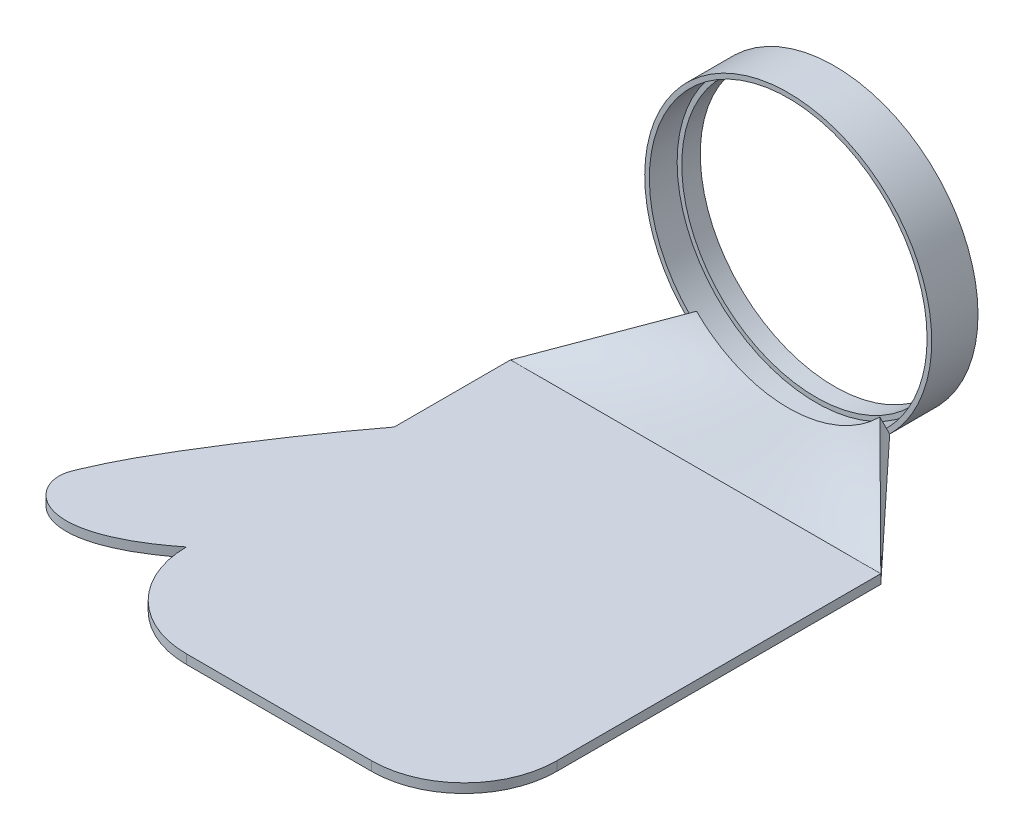
SolidWorks part; units mm, degrees
ref_plane "Front Plane" through (0, 0, 0) normal (0, 0, 1) x (1, 0, 0)
ref_plane "Top Plane" through (0, 0, 0) normal (0, 1, 0) x (1, 0, 0)
ref_plane "Right Plane" through (0, 0, 0) normal (1, 0, 0) x (0, 0, -1)
sketch "Sketch1" plane through (0, 0, 0) normal (0, 0, 1) x (1, 0, 0)
  circle A0 centre (0, 0) radius 15
  circle A1 centre (0, 0) radius 14.5
  dimension "D1" = 30
  dimension "D2" = 0.5
extrude "Boss-Extrude1" add sketch "Sketch1" along normal blind 2
sketch "Sketch2" plane through (0, 0, 2) normal (0, 0, 1) x (1, 0, 0)
  circle A0 centre (0, 0) radius 15
  circle A1 centre (0, 0) radius 15.5
  dimension "D1" = 0.5
extrude "Boss-Extrude2" add sketch "Sketch2" along normal blind 3 and the other way blind 2
sketch "Sketch3" plane through (0, 0, 5) normal (0, 0, 1) x (1, 0, 0)
  line L0 (-9.8995, -9.8995) -> (-10.9602, -10.9602)
  line L1 (9.8995, -9.8995) -> (10.9602, -10.9602)
  line L2 (0, -14) -> (0, -15.5) construction
  arc A0 (-10.9602, -10.9602) -> (10.9602, -10.9602) centre (0, 0) ccw
  arc A1 (-9.8995, -9.8995) -> (9.8995, -9.8995) centre (0, 0) ccw
  dimension "D1" = 28
  dimension "D2" = 90
  dimension "D3" = 45
ref_plane "Plane1" through (0, 0, 15) normal (0, 0, 1) x (1, 0, 0)
sketch "Sketch4" plane through (0, 0, 15) normal (0, 0, 1) x (1, 0, 0)
  line L1 (-20, -15.5) -> (20, -15.5)
  line L2 (-20, -15.5) -> (-20, -14.5)
  line L3 (-20, -14.5) -> (20, -14.5)
  line L4 (20, -15.5) -> (20, -14.5)
  dimension "D1" = 40
  dimension "D2" = 1
  dimension "2" = 20
loft "Loft1" add profiles "Sketch4", "Sketch3"
sketch "Sketch5" plane through (0, 0, 15) normal (0, 0, 1) x (1, 0, 0)
  line L4 (-20, -14.5) -> (-20, -15.5)
  line L5 (-20, -15.5) -> (20, -15.5)
  line L6 (20, -15.5) -> (20, -14.5)
  line L7 (20, -14.5) -> (-20, -14.5)
  line L8 (-20, -14.5) -> (-20, -15.5)
  line L9 (-20, -15.5) -> (20, -15.5)
  line L10 (20, -15.5) -> (20, -14.5)
  line L11 (20, -14.5) -> (-20, -14.5)
  dimension "D1" = 0
extrude "Boss-Extrude3" add sketch "Sketch5" along normal blind 45
fillet "Fillet1" radius 10 2 edges at (-20, -15, 60) (20, -15, 60)
sketch "Sketch6" plane through (0, -14.5, 0) normal (0, 1, 0) x (1, 0, 0)
  line L0 (-20, -50) -> (-20, -15) construction
  line L5 (-20, -15) -> (-20, -50)
  line L6 (-10, -60) -> (10, -60)
  line L7 (20, -50) -> (20, -15)
  line L8 (20, -15) -> (-20, -15)
  line L9 (-20, -27.5616) -> (-20, -50)
  arc A2 (-20, -50) -> (-10, -60) centre (-10, -50) ccw
  arc A3 (10, -60) -> (20, -50) centre (10, -50) ccw
  spline S0 degree 3 poles (-20, -27.5616) (-23.6846, -32.3804) (-30.2536, -42.2867) (-33.1471, -48.6535) (-34.628, -52.2092) (-29.2463, -57.3206) (-20, -50) knots 0 0 0 0 0.304773 0.3504 0.456272 1 1 1 1
  point P2 (-20, -29.4587)
  point P4 (-20, -27.5616)
  dimension "D1" = 0
extrude "Boss-Extrude4" add sketch "Sketch6" against normal blind 1
